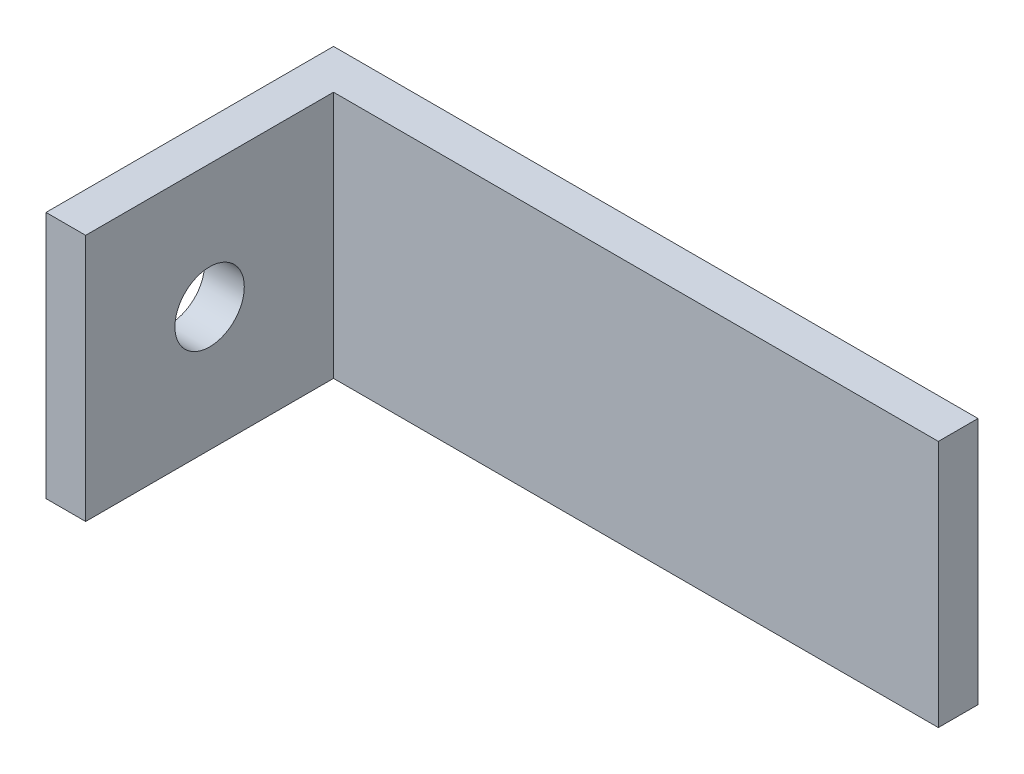
SolidWorks part; units mm, degrees
ref_plane "Front Plane" through (0, 0, 0) normal (0, 0, 1) x (1, 0, 0)
ref_plane "Top Plane" through (0, 0, 0) normal (0, 1, 0) x (1, 0, 0)
ref_plane "Right Plane" through (0, 0, 0) normal (1, 0, 0) x (0, 0, -1)
sketch "Sketch1" plane through (0, 0, 0) normal (0, 0, 1) x (1, 0, 0)
  line L1 (-72.1437, -24.4146) -> (-14.3437, -24.4146)
  line L2 (-72.1437, -24.4146) -> (-72.1437, -48.8146)
  line L3 (-72.1437, -48.8146) -> (-14.3437, -48.8146)
  line L4 (-14.3437, -24.4146) -> (-14.3437, -48.8146)
  dimension "D1" = 24.4
  dimension "D2" = 57.8
extrude "Boss-Extrude1" add sketch "Sketch1" along normal blind 2
sketch "Sketch2" plane through (0, 0, 2) normal (0, 0, 1) x (1, 0, 0)
  line L0 (-72.1437, -48.8146) -> (-14.3437, -48.8146) construction
  line L1 (-72.1437, -24.4146) -> (-68.1437, -24.4146)
  line L2 (-72.1437, -24.4146) -> (-72.1437, -48.8146)
  line L3 (-72.1437, -48.8146) -> (-68.1437, -48.8146)
  line L4 (-68.1437, -24.4146) -> (-68.1437, -48.8146)
  dimension "D1" = 4
extrude "Boss-Extrude2" add sketch "Sketch2" along normal blind 24.4
sketch "Sketch3" plane through (-68.1437, 0, 0) normal (1, 0, 0) x (0, 0, -1)
  circle A0 centre (-14.2, -36.6146) radius 3
  dimension "D1" = 6
extrude "Cut-Extrude1" cut sketch "Sketch3" against normal through all
sketch "Sketch4" plane through (0, 0, 2) normal (0, 0, 1) x (1, 0, 0)
  circle A0 centre (-60.1437, -43.8146) radius 1.5
  circle A1 centre (-20.1437, -43.8146) radius 1.5
  circle A2 centre (-20.1437, -28.8146) radius 1.5
  circle A3 centre (-60.1437, -28.8146) radius 1.5
  dimension "D3" = 3
  dimension "D4" = 2
  dimension "D5" = 2
extrude "Cut-Extrude2" cut sketch "Sketch4" against normal through all
sketch "Sketch5" plane through (0, 0, 0) normal (0, 0, -1) x (-1, 0, 0)
  line L1 (72.1437, -48.8146) -> (14.3437, -48.8146)
  line L2 (72.1437, -48.8146) -> (72.1437, -24.4146)
  line L3 (72.1437, -24.4146) -> (14.3437, -24.4146)
  line L4 (14.3437, -48.8146) -> (14.3437, -24.4146)
extrude "Boss-Extrude3" add sketch "Sketch5" along normal blind 2
sketch "Sketch6" plane through (0, 0, 0) normal (0, 0, 1) x (1, 0, 0)
  circle A0 centre (-60.1437, -28.8146) radius 1.5
  circle A1 centre (-20.1437, -28.8146) radius 1.5
  circle A2 centre (-20.1437, -43.8146) radius 1.5
  circle A3 centre (-60.1437, -43.8146) radius 1.5
  dimension "D1" = 2
  dimension "D2" = 2
extrude "Cut-Extrude3" cut sketch "Sketch6" against normal blind 13
sketch "Sketch8" plane through (0, 0, 2) normal (0, 0, 1) x (1, 0, 0)
  line L1 (-72.1437, -24.4146) -> (-68.1437, -24.4146)
  line L2 (-72.1437, -24.4146) -> (-72.1437, -48.8146)
  line L3 (-72.1437, -48.8146) -> (-68.1437, -48.8146)
  line L4 (-68.1437, -24.4146) -> (-68.1437, -48.8146)
extrude "Boss-Extrude4" add sketch "Sketch8" along normal blind 25
sketch "Sketch9" plane through (0, -48.8146, 0) normal (0, -1, 0) x (-1, 0, 0)
  line L1 (72.1437, -27) -> (68.1437, -27)
  line L2 (68.1437, -27) -> (68.1437, -2)
  line L3 (68.1437, -2) -> (14.3437, -2)
  line L4 (14.3437, -2) -> (14.3437, 2)
  line L5 (14.3437, 2) -> (72.1437, 2)
  line L6 (72.1437, 2) -> (72.1437, -27)
extrude "Boss-Extrude5" add sketch "Sketch9" against normal blind 25
sketch "Sketch10" plane through (0, 0, 2) normal (0, 0, 1) x (1, 0, 0)
  circle A0 centre (-58.1437, -28.8146) radius 1.5
  circle A1 centre (-28.1437, -28.8146) radius 1.5
  circle A2 centre (-28.1437, -43.8146) radius 1.5
  circle A3 centre (-58.1437, -43.8146) radius 1.5
  dimension "D3" = 3
  dimension "D4" = 2
  dimension "D5" = 2
extrude "Cut-Extrude4" cut sketch "Sketch10" against normal through all
sketch "Sketch11" plane through (-68.1437, 0, 0) normal (1, 0, 0) x (0, 0, -1)
  circle A0 centre (-14.5, -36.3146) radius 3.5
  dimension "D1" = 7
extrude "Cut-Extrude5" cut sketch "Sketch11" against normal through all
sketch "Sketch14" plane through (-68.1437, 0, 0) normal (1, 0, 0) x (0, 0, -1)
  line L0 (-2, -48.8146) -> (-2, -23.8146)
  line L1 (-2, -48.8146) -> (2, -48.8146)
  line L2 (-2, -23.8146) -> (2, -23.8146)
  line L3 (2, -48.8146) -> (2, -23.8146)
  dimension "D1" = 4
extrude "Boss-Extrude6" add sketch "Sketch14" against normal blind 4 and the other way blind 61
